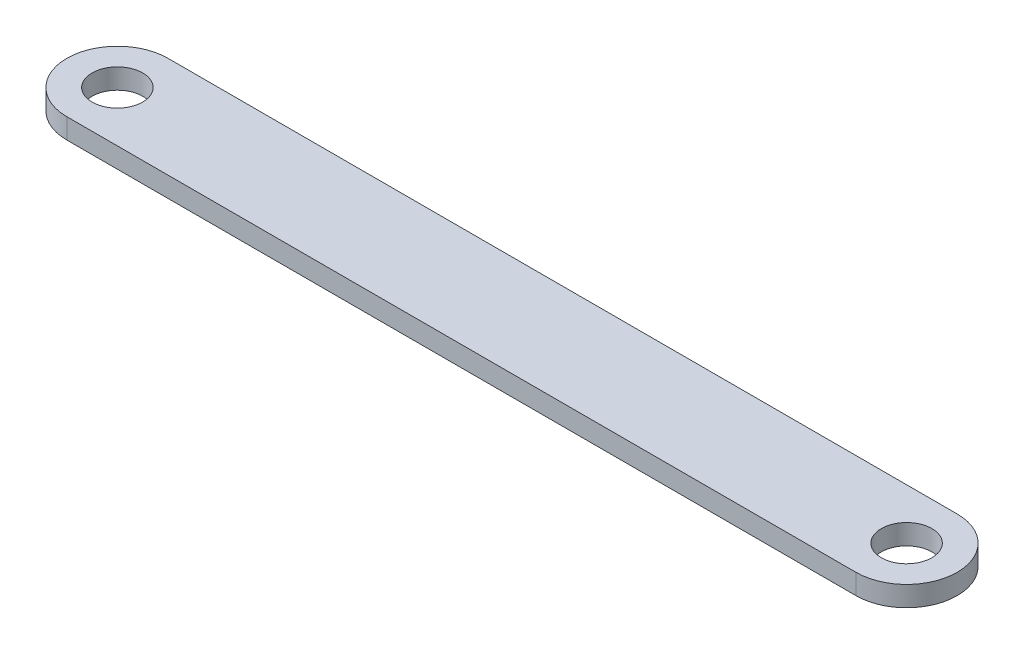
SolidWorks part; units mm, degrees
ref_plane "Front Plane" through (0, 0, 0) normal (0, 0, 1) x (1, 0, 0)
ref_plane "Top Plane" through (0, 0, 0) normal (0, 1, 0) x (1, 0, 0)
ref_plane "Right Plane" through (0, 0, 0) normal (1, 0, 0) x (0, 0, -1)
sketch "Sketch2" plane through (0, 0, 0) normal (0, 1, 0) x (1, 0, 0)
  line L0 (0, 0) -> (0, 12.7) construction
  line L1 (0, 0) -> (0, -12.7) construction
  line L2 (0, 0) -> (12.7, 0) construction
  line L3 (0, 0) -> (-198.2, 0) construction
  line L4 (-198.2, 0) -> (-210.9, 0) construction
  line L5 (-198.2, 0) -> (-198.2, 12.7) construction
  line L6 (-198.2, 0) -> (-198.2, -12.7) construction
  line L7 (-198.2, 12.7) -> (0, 12.7)
  line L8 (-198.2, -12.7) -> (0, -12.7)
  circle A0 centre (0, 0) radius 6.35
  arc A1 (0, 12.7) -> (0, -12.7) centre (0, 0) cw
  circle A2 centre (-198.2, 0) radius 6.35
  arc A3 (-198.2, 12.7) -> (-198.2, -12.7) centre (-198.2, 0) ccw
  point P9 (0, 0)
  point P13 (0, 0)
  point P14 (16.1141, 0)
  point P15 (0, 0)
  point P16 (-210.9, 0)
  dimension "D1" = 12.7
  dimension "D2" = 12.7
  dimension "D6" = 12.7
  dimension "D3" = 12.7
  dimension "D4" = 12.7
  dimension "D5" = 198.2
  dimension "D7" = 12.7
extrude "Boss-Extrude1" add sketch "Sketch2" along normal blind 5.08
